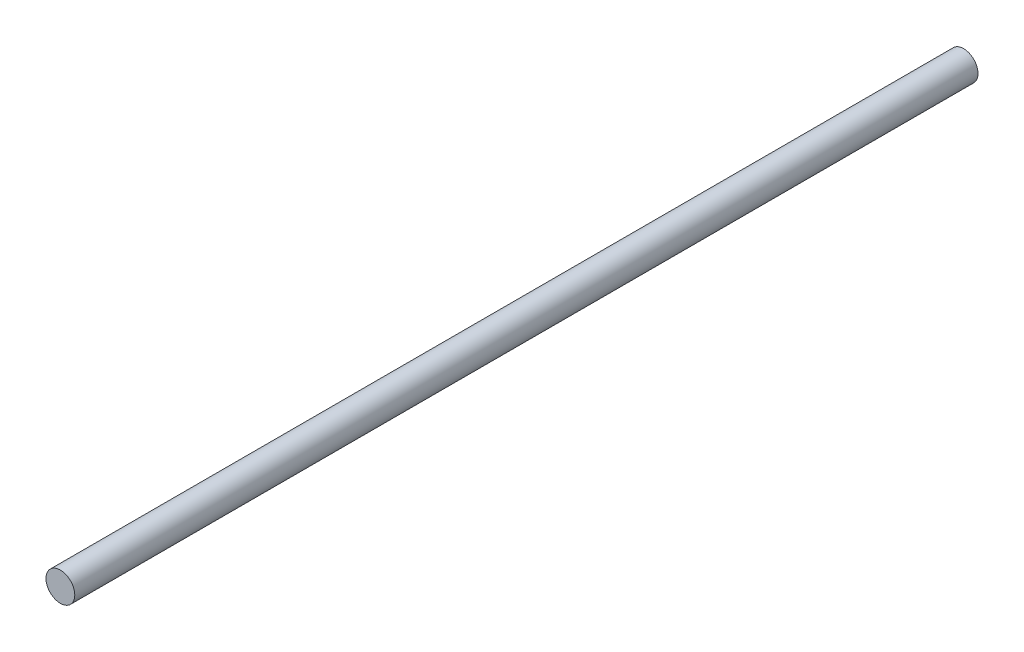
SolidWorks part; units mm, degrees
ref_plane "Front Plane" through (0, 0, 0) normal (0, 0, 1) x (1, 0, 0)
ref_plane "Top Plane" through (0, 0, 0) normal (0, 1, 0) x (1, 0, 0)
ref_plane "Right Plane" through (0, 0, 0) normal (1, 0, 0) x (0, 0, -1)
sketch "Sketch1" plane through (0, 0, 0) normal (0, 0, 1) x (1, 0, 0)
  circle A0 centre (0, 0) radius 12.7
  circle A1 centre (0, 0) radius 12.7 construction
extrude "Boss-Extrude1" add sketch "Sketch1" along normal up to surface (796.2 mm away)
